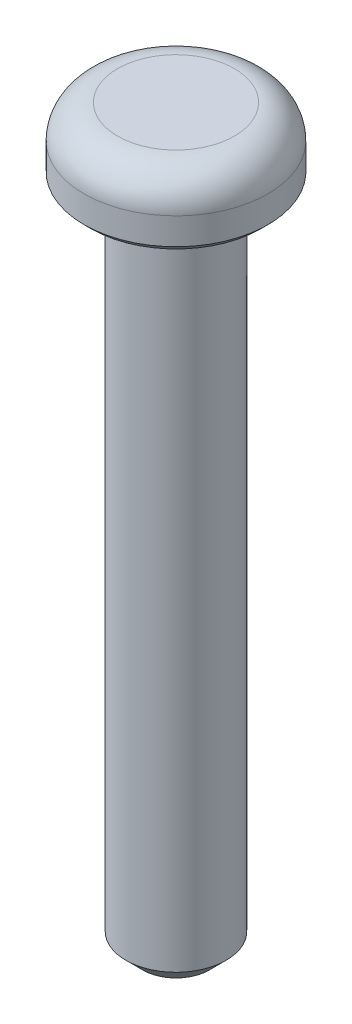
SolidWorks part; units mm, degrees
ref_plane "Front Plane" through (0, 0, 0) normal (0, 0, 1) x (1, 0, 0)
ref_plane "Top Plane" through (0, 0, 0) normal (0, 1, 0) x (1, 0, 0)
ref_plane "Right Plane" through (0, 0, 0) normal (1, 0, 0) x (0, 0, -1)
sketch "Sketch1" plane through (0, 0, 0) normal (0, 0, 1) x (1, 0, 0)
  line L0 (0, 0) -> (0, 22)
  line L1 (0, 22) -> (2.75, 22)
  line L2 (2.75, 22) -> (2.75, 20)
  line L3 (2.75, 20) -> (1.5, 20)
  line L4 (1.5, 20) -> (1.5, 0)
  line L5 (1.5, 0) -> (0, 0)
  dimension "D1" = 1.5
  dimension "D2" = 2.75
  dimension "D3" = 2
  dimension "D4" = 20
revolve "Revolve1" add sketch "Sketch1" angle 360 about L0
fillet "Fillet1" radius 1 1 edges at (0, 22, -2.75)
chamfer "Chamfer1" distance 0.5 angle 45 1 edges at (0, 0, -1.5)
chamfer "Chamfer2" distance 0.2 angle 45 1 edges at (0, 20, -2.75)
